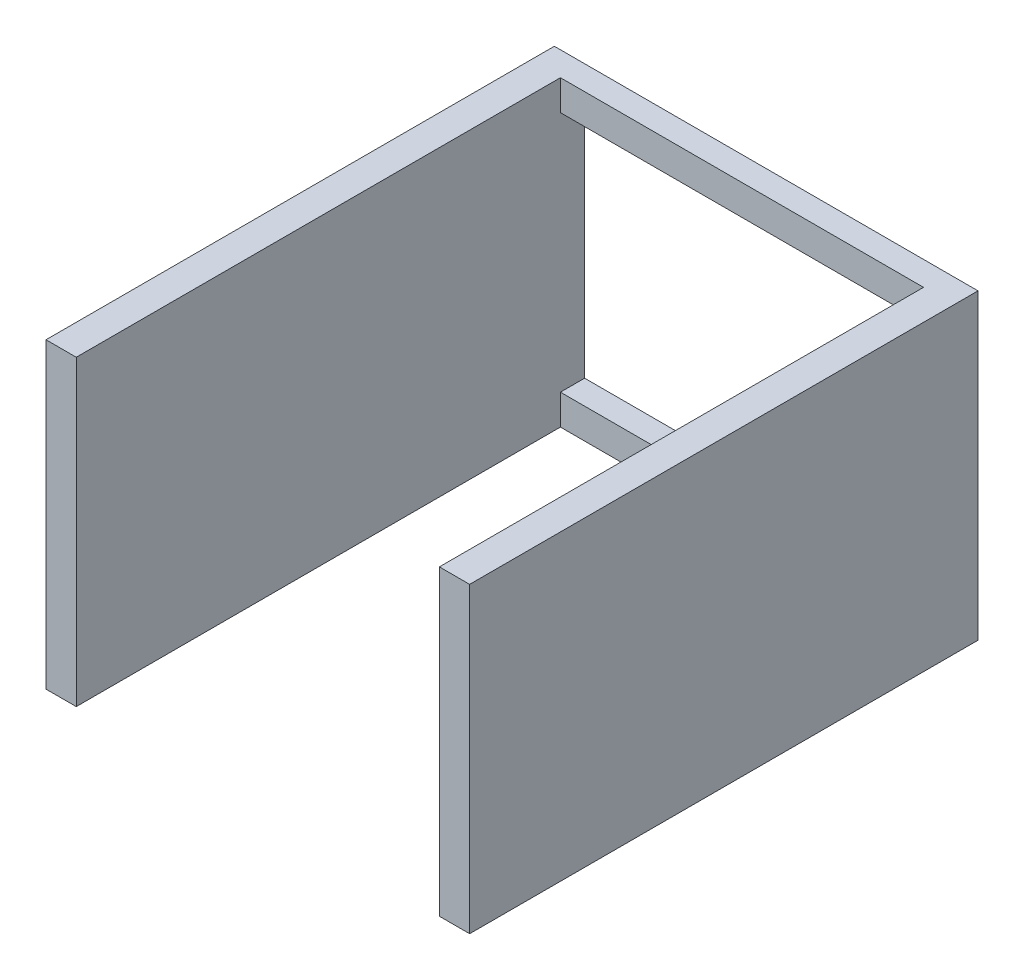
SolidWorks part; units mm, degrees
ref_plane "Alzado" through (0, 0, 0) normal (0, 0, 1) x (1, 0, 0)
ref_plane "Planta" through (0, 0, 0) normal (0, 1, 0) x (1, 0, 0)
ref_plane "Vista lateral" through (0, 0, 0) normal (1, 0, 0) x (0, 0, -1)
sketch "Croquis1" plane through (0, 0, 0) normal (0, 0, 1) x (1, 0, 0)
  line L1 (0, 0) -> (35, 0)
  line L2 (0, 0) -> (0, 25)
  line L3 (0, 25) -> (35, 25)
  line L4 (35, 0) -> (35, 25)
  dimension "D1" = 25
  dimension "D2" = 35
extrude "Saliente-Extruir2" add sketch "Croquis1" along normal blind 42
sketch "Croquis3" plane through (0, 0, 42) normal (0, 0, 1) x (1, 0, 0)
  line L0 (35, 25) -> (0, 25) construction
  line L1 (2.5, 2.5) -> (32.5, 2.5)
  line L2 (2.5, 2.5) -> (2.5, 22.5)
  line L3 (2.5, 22.5) -> (32.5, 22.5)
  line L4 (32.5, 2.5) -> (32.5, 22.5)
  line L5 (35, 0) -> (35, 25) construction
  line L6 (0, 0) -> (35, 0) construction
  line L7 (0, 25) -> (0, 0) construction
  dimension "D1" = 2.5
  dimension "D2" = 2.5
  dimension "D3" = 2.5
  dimension "D4" = 2.5
extrude "Cortar-Extruir1" cut sketch "Croquis3" against normal through all
sketch "Croquis4" plane through (0, 25, 0) normal (0, 1, 0) x (1, 0, 0)
  line L1 (2.5, -42) -> (32.5, -42)
  line L2 (2.5, -42) -> (2.5, -2)
  line L3 (2.5, -2) -> (32.5, -2)
  line L4 (32.5, -42) -> (32.5, -2)
  dimension "D1" = 40
extrude "Cortar-Extruir2" cut sketch "Croquis4" against normal through all
ref_plane "Plano1" through (0, 0, -100) normal (0, 0, -1) x (-1, 0, 0)
sketch "Croquis5" plane through (0, 0, -100) normal (0, 0, -1) x (-1, 0, 0)
  line L0 (-2.5, 22.5) -> (-2.5, 2.5) construction
  line L3 (-32.5, 22.5) -> (-2.5, 22.5) construction
  circle A0 centre (-17.5, 12.5) radius 27.933 construction
  ellipse E0 centre (-17.5, -7) end of major axis (2.5, -7) minor radius 12.5 construction
  ellipse E1 centre (-34.3875, 22.25) end of major axis (-24.3875, 39.5705) minor radius 12.5
  ellipse E2 centre (-0.6125, 22.25) end of major axis (-10.6125, 39.5705) minor radius 12.5
  point P1 (-17.5, 32)
  point P7 (-17.5, 13.508)
  point P8 (0, 0)
  point P9 (-17.5227, 14.2612)
  point P12 (-2.5, 12.5)
  point P15 (-17.5, 22.5)
  point P30 (-17.5, 12.5)
  dimension "D1" = 40
  dimension "D2" = 25
  dimension "D3" = 7
  dimension "D4" = 3
ref_plane "Plano2" through (0, 0, -40) normal (0, 0, -1) x (-1, 0, 0)
